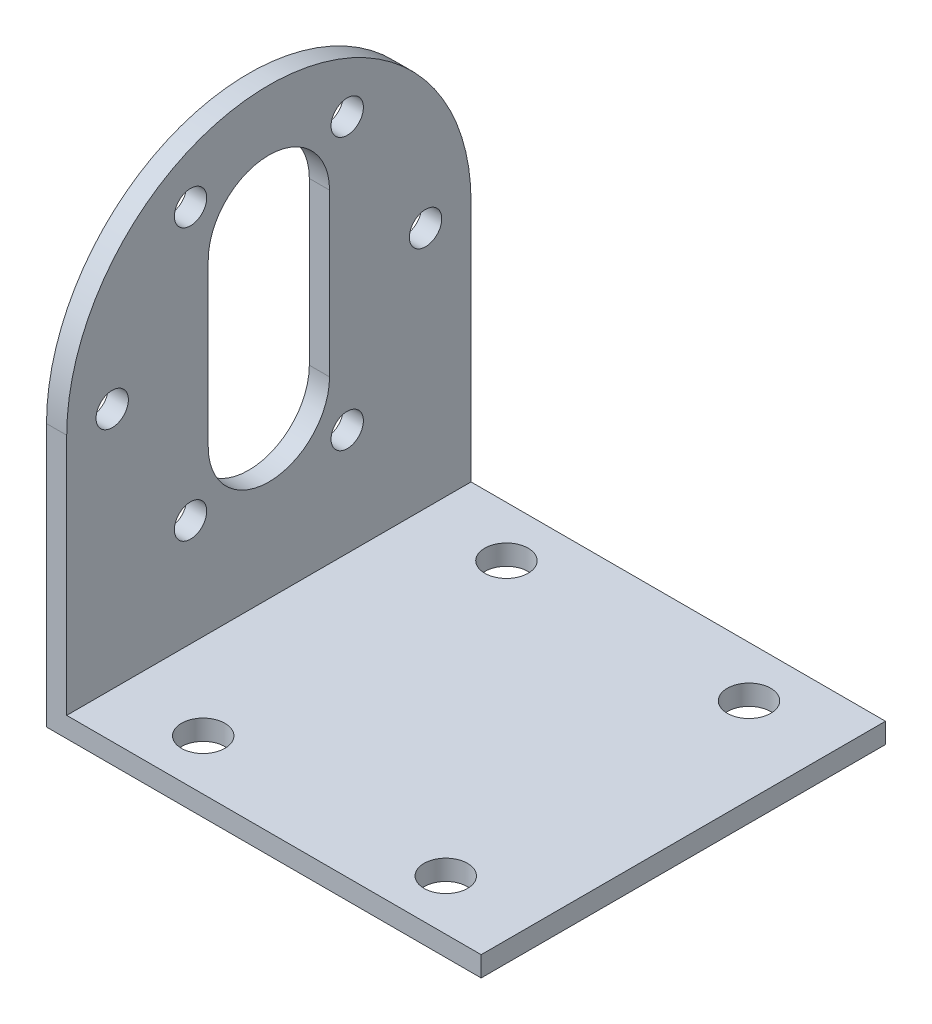
SolidWorks part; units mm, degrees
ref_plane "前视基准面" through (0, 0, 0) normal (0, 0, 1) x (1, 0, 0)
ref_plane "上视基准面" through (0, 0, 0) normal (0, 1, 0) x (1, 0, 0)
ref_plane "右视基准面" through (0, 0, 0) normal (1, 0, 0) x (0, 0, -1)
sketch "草图1" plane through (0, 0, 0) normal (0, 1, 0) x (1, 0, 0)
  line L0 (-35.878, 0) -> (46.133, 0) construction
  line L1 (-21.5, -20) -> (21.5, -20)
  line L2 (-21.5, -20) -> (-21.5, 20)
  line L3 (-21.5, 20) -> (21.5, 20)
  line L4 (21.5, -20) -> (21.5, 20)
  line L5 (-21.5, -20) -> (21.5, 20) construction
  line L6 (-21.5, 20) -> (21.5, -20) construction
  line L7 (1, 32.9677) -> (1, -31.7553) construction
  line L8 (0, 34.968) -> (0, -34.327) construction
  circle A0 centre (13, 15) radius 2.15
  circle A1 centre (13, -15) radius 2.15
  circle A2 centre (-11, 15) radius 2.15
  circle A3 centre (-11, -15) radius 2.15
  point P0 (0, 0)
  dimension "D3" = 4.3
  dimension "D4" = 24
  dimension "D5" = 30
  dimension "D1" = 43
  dimension "D2" = 40
  dimension "D6" = 1
extrude "凸台-拉伸1" add sketch "草图1" along normal blind 2
sketch "草图3" plane through (-21.5, 0, 0) normal (-1, 0, 0) x (0, 0, 1)
  line L0 (-20, 0) -> (-20, 26)
  line L1 (20, 26) -> (20, 0)
  line L2 (-20, 0) -> (20, 0) construction
  line L3 (40.3018, 26) -> (-34.7832, 26) construction
  line L4 (0, 56.2834) -> (0, -27.9706) construction
  line L5 (-6, 18) -> (-6, 34)
  line L6 (6, 18) -> (6, 34)
  line L7 (-20, 0) -> (20, 0)
  arc A0 (-20, 26) -> (20, 26) centre (0, 26) cw
  circle A1 centre (0, 26) radius 15.5 construction
  circle A2 centre (-15.5, 26) radius 1.6
  circle A3 centre (-7.75, 39.4234) radius 1.6
  circle A4 centre (7.75, 39.4234) radius 1.6
  circle A5 centre (15.5, 26) radius 1.6
  circle A6 centre (7.75, 12.5766) radius 1.6
  circle A7 centre (-7.75, 12.5766) radius 1.6
  arc A8 (-6, 34) -> (6, 34) centre (0, 34) cw
  arc A9 (-6, 18) -> (6, 18) centre (0, 18) ccw
  point P26 (0, 26)
  point P34 (6, 26)
  point P36 (-6, 26)
  dimension "D2" = 3.2
  dimension "D3" = 31
  dimension "D5" = 8
  dimension "D6" = 6
  dimension "D1" = 26
  dimension "D4" = 6
extrude "凸台-拉伸2" add sketch "草图3" against normal blind 2
